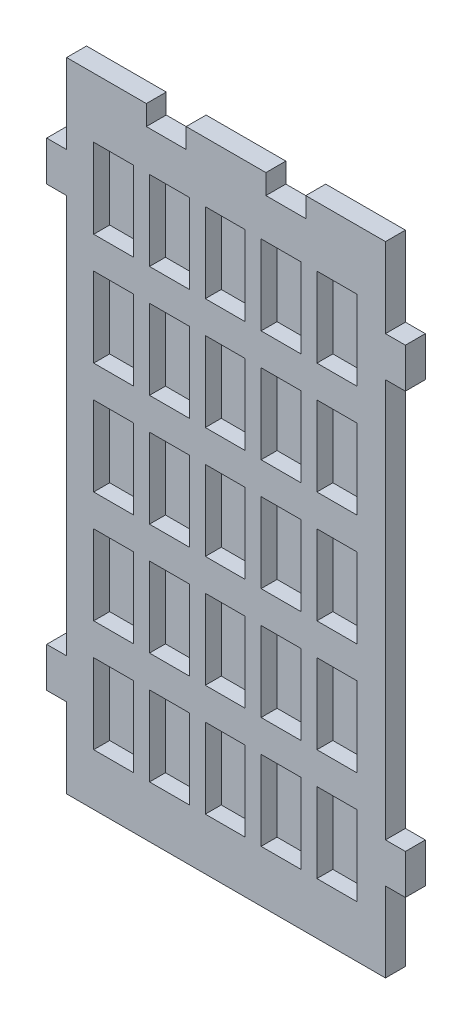
SolidWorks part; units mm, degrees
ref_plane "Front Plane" through (0, 0, 0) normal (0, 0, 1) x (1, 0, 0)
ref_plane "Top Plane" through (0, 0, 0) normal (0, 1, 0) x (1, 0, 0)
ref_plane "Right Plane" through (0, 0, 0) normal (1, 0, 0) x (0, 0, -1)
sketch "Sketch1" plane through (0, 0, 0) normal (0, 0, 1) x (1, 0, 0)
  line L0 (19.05, 0) -> (31.75, 0)
  line L1 (0, 0) -> (12.7, 0)
  line L2 (0, 0) -> (0, -12.7)
  line L3 (0, -101.6) -> (12.7, -101.6)
  line L4 (50.8, -19.05) -> (50.8, -82.55)
  line L5 (38.1, 0) -> (50.8, 0)
  line L6 (12.7, 0) -> (12.7, -3.175)
  line L7 (12.7, -3.175) -> (19.05, -3.175)
  line L8 (19.05, 0) -> (19.05, -3.175)
  line L9 (0, -19.05) -> (0, -82.55)
  line L10 (31.75, 0) -> (31.75, -3.175)
  line L11 (31.75, -3.175) -> (38.1, -3.175)
  line L12 (38.1, 0) -> (38.1, -3.175)
  line L13 (50.8, -12.7) -> (53.975, -12.7)
  line L14 (50.8, -88.9) -> (50.8, -101.6)
  line L15 (50.8, -19.05) -> (53.975, -19.05)
  line L16 (53.975, -12.7) -> (53.975, -19.05)
  line L17 (50.8, -82.55) -> (53.975, -82.55)
  line L18 (63.5, -101.6) -> (50.8, -101.6)
  line L19 (50.8, -88.9) -> (53.975, -88.9)
  line L20 (53.975, -82.55) -> (53.975, -88.9)
  line L21 (12.7, -101.6) -> (63.5, -101.6)
  line L25 (0, -88.9) -> (0, -101.6)
  line L29 (0, -88.9) -> (-3.175, -88.9)
  line L31 (0, -82.55) -> (-3.175, -82.55)
  line L32 (-3.175, -88.9) -> (-3.175, -82.55)
  line L33 (0, -19.05) -> (-3.175, -19.05)
  line L34 (50.8, 0) -> (50.8, -12.7)
  line L35 (0, -12.7) -> (-3.175, -12.7)
  line L36 (-3.175, -19.05) -> (-3.175, -12.7)
  dimension "D3" = 12.7
  dimension "D4" = 6.35
  dimension "D5" = 3.175
  dimension "D6" = 6.35
  dimension "D7" = 3.175
  dimension "D8" = 12.7
  dimension "D9" = 101.6
  dimension "D10" = 6.35
  dimension "D11" = 3.175
  dimension "D12" = 3.175
  dimension "D13" = 6.35
  dimension "D14" = 12.7
  dimension "D15" = 50.8
  dimension "D21" = 3.175
  dimension "D22" = 6.35
  dimension "D23" = 12.7
  dimension "D24" = 12.7
  dimension "D25" = 6.35
  dimension "D26" = 3.175
  dimension "D27" = 3.175
  dimension "D29" = 3.175
  dimension "D30" = 12.7
extrude "Boss-Extrude1" add sketch "Sketch1" along normal blind 3.175
sketch "Sketch2" plane through (0, 0, 3.175) normal (0, 0, 1) x (1, 0, 0)
  line L0 (12.7, -3.175) -> (19.05, -3.175) construction
  line L1 (4.318, -9.525) -> (10.668, -9.525)
  line L2 (4.318, -9.525) -> (4.318, -22.225)
  line L3 (4.318, -22.225) -> (10.668, -22.225)
  line L4 (10.668, -9.525) -> (10.668, -22.225)
  line L5 (4.318, -9.525) -> (10.668, -22.225) construction
  line L6 (4.318, -22.225) -> (10.668, -9.525) construction
  line L7 (0, -19.05) -> (0, -82.55) construction
  point P0 (7.493, -15.875)
  dimension "D1" = 6.35
  dimension "D2" = 6.35
  dimension "D3" = 12.7
  dimension "D4" = 4.318
extrude "Cut-Extrude1" cut sketch "Sketch2" against normal blind 2.54
pattern_linear "LPattern1" count 5 spacing 8.89 along (1, 0, 0) count 5 spacing 17.78 along (0, -1, 0) of "Cut-Extrude1"
